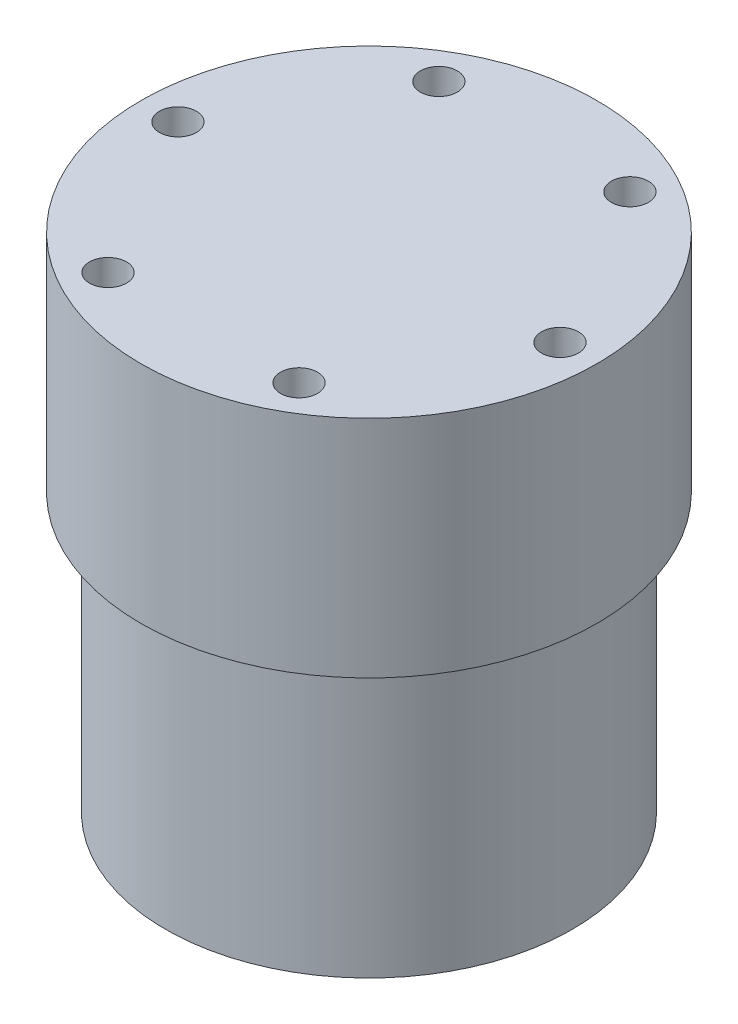
SolidWorks part; units mm, degrees
ref_plane "Front Plane" through (0, 0, 0) normal (0, 0, 1) x (1, 0, 0)
ref_plane "Top Plane" through (0, 0, 0) normal (0, 1, 0) x (1, 0, 0)
ref_plane "Right Plane" through (0, 0, 0) normal (1, 0, 0) x (0, 0, -1)
sketch "Sketch1" plane through (0, 0, 0) normal (0, 1, 0) x (1, 0, 0)
  circle A0 centre (0, 0) radius 16.5
  dimension "D1" = 33
extrude "Boss-Extrude1" add sketch "Sketch1" along normal blind 22.5
sketch "Sketch2" plane through (0, 22.5, 0) normal (0, 1, 0) x (1, 0, 0)
  circle A0 centre (0, 0) radius 18.5
  dimension "D1" = 37
extrude "Boss-Extrude2" add sketch "Sketch2" along normal blind 18.25
sketch "Sketch7" plane through (0, 40.75, 0) normal (0, 1, 0) x (1, 0, 0)
  line L0 (-18.5, 0) -> (18.5, 0) construction
  line L1 (0, -18.5) -> (0, 18.5) construction
  line L2 (0, 0) -> (9.25, 16.0215) construction
  circle A0 centre (0, 0) radius 18.5 construction
  circle A1 centre (15.5, 0) radius 1.5
  circle A2 centre (7.75, 13.4234) radius 1.5
  circle A3 centre (-15.5, 0) radius 1.5
  circle A4 centre (-7.75, 13.4234) radius 1.5
  circle A5 centre (7.75, -13.4234) radius 1.5
  circle A6 centre (-7.75, -13.4234) radius 1.5
  dimension "D1" = 3
  dimension "D3" = 3
  dimension "D2" = 30
  dimension "D4" = 31
  dimension "D5" = 31
extrude "Cut-Extrude2" cut sketch "Sketch7" against normal blind 6
sketch "Sketch8" plane through (0, 40.75, 0) normal (0, 1, 0) x (1, 0, 0)
  line L0 (0, 0) -> (0, 18.5) construction
  circle A0 centre (0, 0) radius 18.5 construction
  circle A1 centre (0, 7) radius 4.8712
  point P8 (0, 0)
  dimension "D1" = 7
